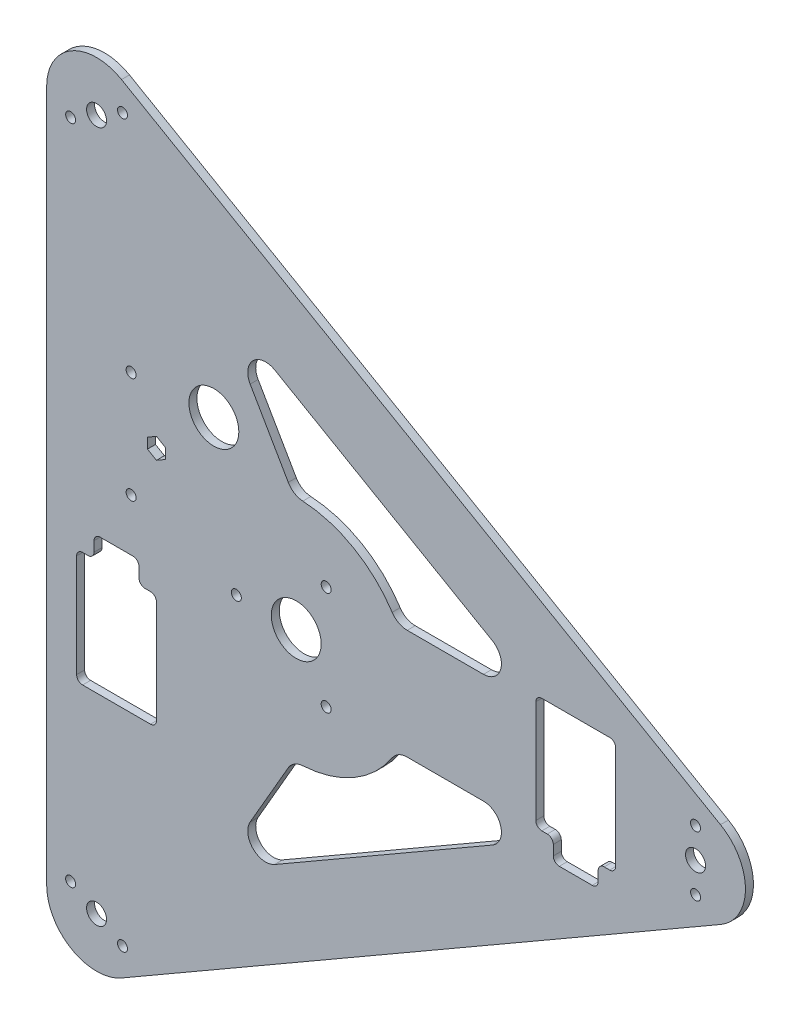
SolidWorks part; units mm, degrees
other "Frame4"
material "Hexcel AS4C (3000 Filaments)"
ref_plane "Front" through (0, 0, 0) normal (0, 0, 1) x (1, 0, 0)
ref_plane "Top" through (0, 0, 0) normal (0, 1, 0) x (1, 0, 0)
ref_plane "Right" through (0, 0, 0) normal (1, 0, 0) x (0, 0, -1)
sketch "BoardSke" plane through (0, 0, 0) normal (0, 0, 1) x (1, 0, 0)
  line L1 (42.5, 4.3301) -> (-17.5, 38.9711)
  line L2 (-25, 34.641) -> (-25, -34.641)
  line L3 (-17.5, -38.9711) -> (42.5, -4.3301)
  circle A0 centre (0, 0) radius 25 construction
  arc A1 (-25, -34.641) -> (-17.5, -38.9711) centre (-20, -34.641) ccw
  arc A2 (42.5, 4.3301) -> (42.5, -4.3301) centre (40, 0) cw
  arc A3 (-17.5, 38.9711) -> (-25, 34.641) centre (-20, 34.641) ccw
  dimension "D1" = 50
  dimension "D2" = 5
extrude "Board" add sketch "BoardSke" along normal blind 0.8 separate body
sketch "CutSke" plane through (0, 0, 0.8) normal (0, 0, 1) x (1, 0, 0)
  line L0 (31.0718, 3) -> (9.1652, 3) construction
  line L1 (31.5718, 4.866) -> (-11.5718, 29.775) construction
  line L2 (-12.9378, 28.409) -> (-1.9845, 9.4373) construction
  line L3 (0, 0) -> (-22.5, 38.9711) construction
  line L4 (0, 0) -> (45, 0) construction
  line L5 (0, 0) -> (-22.5, -38.9711) construction
  line L6 (42.5, 4.3301) -> (-17.5, 38.9711) construction
  line L7 (31.0718, -3) -> (9.1652, -3) construction
  line L8 (-11.5718, -29.775) -> (31.5718, -4.866) construction
  line L9 (-12.9378, -28.409) -> (-1.9845, -9.4373) construction
  line L10 (-18.134, -25.409) -> (-7.1807, -6.4373) construction
  line L11 (-20, 24.909) -> (-20, -24.909) construction
  line L12 (-18.134, 25.409) -> (-7.1807, 6.4373) construction
  line L13 (-7.9737, 24.8109) -> (-0.2866, 11.4964)
  line L14 (25.4737, 5.5) -> (-7.9737, 24.8109)
  line L15 (25.4737, 5.5) -> (10.0995, 5.5)
  line L16 (25.4737, -5.5) -> (10.0995, -5.5)
  line L17 (-7.9737, -24.8109) -> (-0.2866, -11.4964)
  line L18 (-7.9737, -24.8109) -> (25.4737, -5.5)
  arc A0 (8.2486, 3.6) -> (-1.0066, 8.9435) centre (0, 0) ccw construction
  arc A1 (-17.5, 38.9711) -> (-25, 34.641) centre (-20, 34.641) ccw construction
  arc A2 (42.5, -4.3301) -> (42.5, 4.3301) centre (40, 0) ccw construction
  arc A3 (-25, -34.641) -> (-17.5, -38.9711) centre (-20, -34.641) ccw construction
  arc A4 (31.0718, 3) -> (31.5718, 4.866) centre (31.0718, 4) ccw construction
  arc A5 (-11.5718, 29.775) -> (-12.9378, 28.409) centre (-12.0718, 28.909) ccw construction
  arc A6 (-1.9845, 9.4373) -> (-1.0066, 8.9435) centre (-1.1185, 9.9373) ccw construction
  arc A7 (9.1652, 3) -> (8.2486, 3.6) centre (9.1652, 4) cw construction
  arc A8 (-1.0066, -8.9435) -> (8.2486, -3.6) centre (0, 0) ccw construction
  arc A9 (-1.9845, -9.4373) -> (-1.0066, -8.9435) centre (-1.1185, -9.9373) cw construction
  arc A10 (9.1652, -3) -> (8.2486, -3.6) centre (9.1652, -4) ccw construction
  arc A11 (31.5718, -4.866) -> (31.0718, -3) centre (31.0718, -4) ccw construction
  arc A12 (-12.9378, -28.409) -> (-11.5718, -29.775) centre (-12.0718, -28.909) ccw construction
  arc A13 (-7.242, 5.3435) -> (-7.242, -5.3435) centre (0, 0) ccw construction
  arc A14 (-7.1807, 6.4373) -> (-7.242, 5.3435) centre (-8.0467, 5.9373) cw construction
  arc A15 (-7.1807, -6.4373) -> (-7.242, -5.3435) centre (-8.0467, -5.9373) ccw construction
  arc A16 (-20, -24.909) -> (-18.134, -25.409) centre (-19, -24.909) ccw construction
  arc A17 (-18.134, 25.409) -> (-20, 24.909) centre (-19, 24.909) ccw construction
  arc A18 (10.0995, 5.5) -> (-0.2866, 11.4964) centre (0, 0) ccw
  arc A19 (-0.2866, 11.4964) -> (-0.2866, 11.4964) centre (-0.2866, 11.4964) ccw
  arc A20 (-7.9737, 24.8109) -> (-7.9737, 24.8109) centre (-7.9737, 24.8109) ccw
  arc A21 (25.4737, 5.5) -> (25.4737, 5.5) centre (25.4737, 5.5) ccw
  arc A22 (10.0995, 5.5) -> (10.0995, 5.5) centre (10.0995, 5.5) cw
  arc A23 (10.0995, -5.5) -> (10.0995, -5.5) centre (10.0995, -5.5) ccw
  arc A24 (-0.2866, -11.4964) -> (10.0995, -5.5) centre (0, 0) ccw
  arc A25 (-0.2866, -11.4964) -> (-0.2866, -11.4964) centre (-0.2866, -11.4964) cw
  arc A26 (-7.9737, -24.8109) -> (-7.9737, -24.8109) centre (-7.9737, -24.8109) ccw
  arc A27 (25.4737, -5.5) -> (25.4737, -5.5) centre (25.4737, -5.5) ccw
  point P55 (0, 0)
  dimension "D1" = 18
  dimension "D5" = 1
  dimension "D6" = 1
  dimension "D2" = 3
  dimension "D3" = 3
  dimension "D4" = 5
  dimension "D8" = 2.5
  dimension "D9" = 2.5
  dimension "D7" = 3
extrude "Cut" cut sketch "CutSke" against normal through all
sketch "HolesSke" plane through (0, 0, 0.8) normal (0, 0, 1) x (1, 0, 0)
  circle A0 centre (-6, 0) radius 0.5
  circle A1 centre (3, 5.1962) radius 0.5
  circle A2 centre (3, -5.1962) radius 0.5
  circle A3 centre (0, 0) radius 2.5
  point P9 (0, 0)
  dimension "D2" = 6
  dimension "D1" = 1
  dimension "D4" = 5
  dimension "D3" = 3
extrude "Holes" cut sketch "HolesSke" against normal through all
sketch "Holes2Ske" plane through (0, 0, 0.8) normal (0, 0, 1) x (1, 0, 0)
  line L1 (0, 0) -> (40, 0) construction
  circle A2 centre (40, 0) radius 1
  circle A4 centre (-20, -34.641) radius 1
  circle A6 centre (-20, 34.641) radius 1
  point P18 (0, 0)
  dimension "D1" = 40
  dimension "D2" = 2
  dimension "D4" = 3
extrude "Holes2" cut sketch "Holes2Ske" against normal through all
sketch "Holes3Ske" plane through (0, 0, 0.8) normal (0, 0, 1) x (1, 0, 0)
  line L0 (40, 3) -> (40, -3) construction
  circle A0 centre (40, 0) radius 1 construction
  circle A1 centre (40, 0) radius 1 construction
  circle A2 centre (40, 3) radius 0.5
  circle A3 centre (40, -3) radius 0.5
  circle A4 centre (-22.5981, -33.141) radius 0.5
  circle A5 centre (-17.4019, -36.141) radius 0.5
  circle A6 centre (-17.4019, 36.141) radius 0.5
  circle A7 centre (-22.5981, 33.141) radius 0.5
  point P19 (0, 0)
  dimension "D1" = 1
  dimension "D2" = 3
  dimension "D3" = 3
extrude "Holes3" cut sketch "Holes3Ske" against normal through all
sketch "Holes4Ske" plane through (0, 0, 0.8) normal (0, 0, 1) x (1, 0, 0)
  line L0 (-16.5389, 14.0447) -> (-14.0018, 8.7292) construction
  line L1 (0, 0) -> (-20, 34.641) construction
  line L2 (-14.0018, 8.7292) -> (-16.5389, 3.4136) construction
  line L3 (-13.1018, 8.2096) -> (-13.1018, 9.2488)
  line L4 (-13.1018, 9.2488) -> (-14.0018, 9.7684)
  line L5 (-14.0018, 9.7684) -> (-14.9018, 9.2488)
  line L6 (-14.9018, 9.2488) -> (-14.9018, 8.2096)
  line L7 (-14.9018, 8.2096) -> (-14.0018, 7.6899)
  line L8 (-14.0018, 7.6899) -> (-13.1018, 8.2096)
  circle A0 centre (0, 0) radius 12.5 construction
  circle A1 centre (-8.25, 14.2894) radius 4 construction
  circle A2 centre (-8.25, 14.2894) radius 2.5
  circle A3 centre (-14.0018, 8.7292) radius 4 construction
  circle A4 centre (-14.0018, 8.7292) radius 0.9 construction
  circle A5 centre (-16.5389, 14.0447) radius 0.5
  circle A6 centre (-16.5389, 3.4136) radius 0.5
  dimension "D1" = 25
  dimension "D2" = 8
  dimension "D3" = 5
  dimension "D4" = 8
  dimension "D8" = 1
  dimension "D5" = 1.8
  dimension "D6" = 128.97
  dimension "D7" = 5.89
extrude "Holes4" cut sketch "Holes4Ske" against normal through all
fillet "Fillet1" radius 1.8 8 edges at (-7.9737, -24.8109, 0.4) (-0.2866, -11.4964, 0.4) (10.0995, -5.5, 0.4) (25.4737, -5.5, 0.4) (25.4737, 5.5, 0.4) (10.0995, 5.5, 0.4) (-0.2866, 11.4964, 0.4) (-7.9737, 24.8109, 0.4)
sketch "ServoSetSke" plane through (0, 0, 0.8) normal (0, 0, 1) x (1, 0, 0)
  line L8 (30.25, -5.1552) -> (32, -5.1552)
  line L9 (30.25, -7.3552) -> (32.0026, -10.3908) construction
  line L16 (-15.75, -4) -> (-14, -4)
  line L22 (24, -5.1552) -> (25.75, -5.1552)
  line L23 (24, -5.1552) -> (24, 6.3448)
  line L24 (-22, -4) -> (-20.25, -4)
  line L30 (-22, -4) -> (-22, -15.5)
  line L31 (-22, -15.5) -> (-14, -15.5)
  line L32 (-14, -4) -> (-14, -15.5)
  line L33 (-22, -4) -> (-14, -15.5) construction
  line L34 (-22, -15.5) -> (-14, -4) construction
  line L35 (-20.25, -1.8) -> (-15.75, -1.8)
  line L36 (-20.25, -1.8) -> (-20.25, -4)
  line L38 (-15.75, -1.8) -> (-15.75, -4)
  line L39 (-20.25, -1.8) -> (-15.75, -4) construction
  line L40 (-20.25, -4) -> (-15.75, -1.8) construction
  line L41 (24, 6.3448) -> (32, 6.3448)
  line L42 (32, -5.1552) -> (32, 6.3448)
  line L43 (25.75, -7.3552) -> (30.25, -7.3552)
  line L44 (25.75, -7.3552) -> (25.75, -5.1552)
  line L45 (30.25, -7.3552) -> (30.25, -5.1552)
  line L46 (28, 6.3448) -> (28, -7.3552) construction
  line L47 (-17.5, -38.9711) -> (42.5, -4.3301) construction
  line L48 (32, 6.3448) -> (33.7526, 9.3804) construction
  line L49 (42.5, 4.3301) -> (-17.5, 38.9711) construction
  point P18 (-18, -2.9)
  point P19 (-18, -9.75)
  dimension "D2" = 4.5
  dimension "D3" = 4
  dimension "D4" = 18
  dimension "D5" = 11.5
  dimension "D6" = 2.2
  dimension "D7" = 8
  dimension "D8" = 4.5
  dimension "D9" = 2.2
  dimension "D10" = 8
  dimension "D11" = 11.5
  dimension "D12" = 28
  dimension "D13" = 3.5052
extrude "ServoSet" cut sketch "ServoSetSke" against normal blind 10
fillet "Fillet2" radius 0.6 16 edges at (30.25, -7.3552, 0.4) (25.75, -7.3552, 0.4) (-15.75, -1.8, 0.4) (-20.25, -1.8, 0.4) (32, 6.3448, 0.4) (24, 6.3448, 0.4) (24, -5.1552, 0.4) (25.75, -5.1552, 0.4) (32, -5.1552, 0.4) (30.25, -5.1552, 0.4) (-14, -15.5, 0.4) (-22, -15.5, 0.4) (-14, -4, 0.4) (-22, -4, 0.4) (-15.75, -4, 0.4) (-20.25, -4, 0.4)
